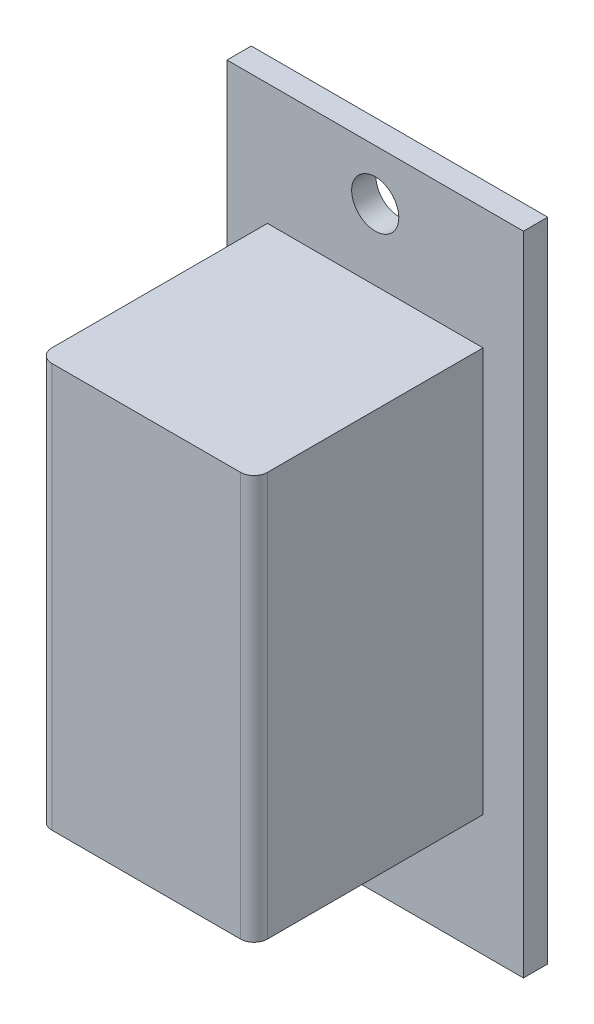
SolidWorks part; units mm, degrees
ref_plane "前视基准面" through (0, 0, 0) normal (0, 0, 1) x (1, 0, 0)
ref_plane "上视基准面" through (0, 0, 0) normal (0, 1, 0) x (1, 0, 0)
ref_plane "右视基准面" through (0, 0, 0) normal (1, 0, 0) x (0, 0, -1)
sketch "草图1" plane through (0, 0, 0) normal (0, 0, 1) x (1, 0, 0)
  line L0 (0, 48.626) -> (0, -83.7004) construction
  line L1 (-92.2698, 0) -> (95.8569, 0) construction
  line L2 (-11, 24) -> (11, 24)
  line L3 (-11, 24) -> (-11, -24)
  line L4 (-11, -24) -> (11, -24)
  line L5 (11, -24) -> (11, 24)
  circle A0 centre (0, 20.25) radius 1.75
  circle A1 centre (0, -20.25) radius 1.75
  dimension "D3" = 3.75
  dimension "D4" = 3.5
  dimension "D1" = 22
  dimension "D2" = 40.5
extrude "拉伸1" add sketch "草图1" along normal blind 1.8
sketch "草图2" plane through (0, 0, 1.8) normal (0, 0, 1) x (1, 0, 0)
  line L0 (0, 37.5456) -> (0, -35.199) construction
  line L1 (-34.3867, 0) -> (34.7477, 0) construction
  line L2 (-8, 15) -> (8, 15)
  line L3 (-8, 15) -> (-8, -15)
  line L4 (-8, -15) -> (8, -15)
  line L5 (8, -15) -> (8, 15)
  dimension "D1" = 16
  dimension "D2" = 30
extrude "拉伸2" add sketch "草图2" along normal blind 17
fillet "圆角1" radius 1 2 edges at (-8, 0, 18.8) (8, 0, 18.8)
